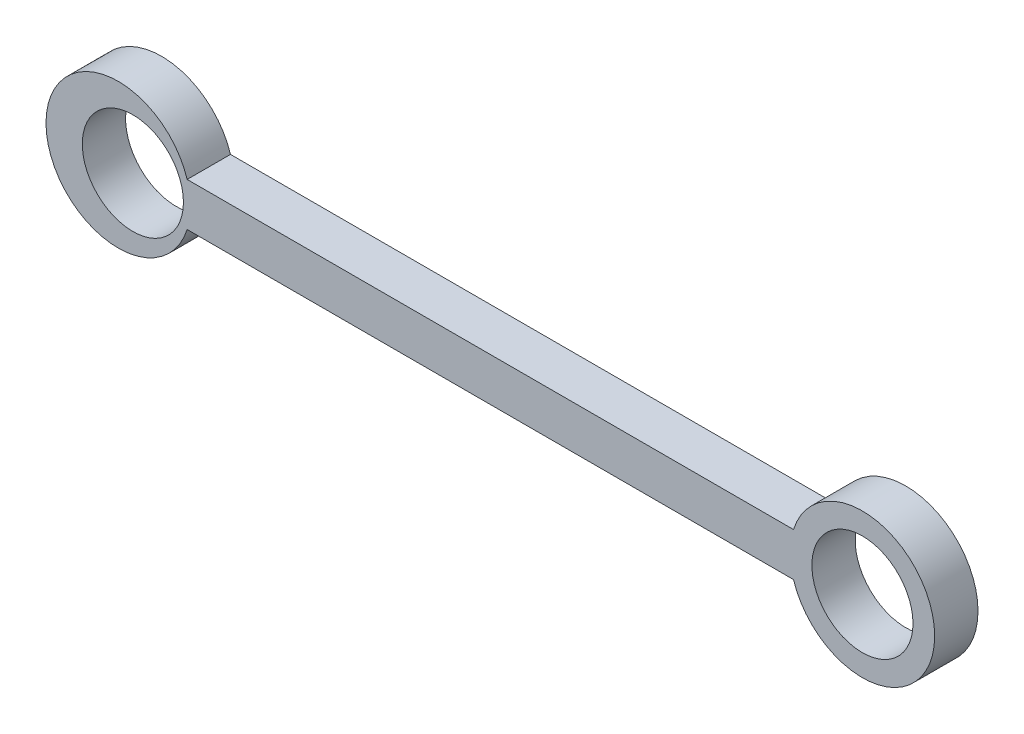
SolidWorks part; units mm, degrees
ref_plane "Front Plane" through (0, 0, 0) normal (0, 0, 1) x (1, 0, 0)
ref_plane "Top Plane" through (0, 0, 0) normal (0, 1, 0) x (1, 0, 0)
ref_plane "Right Plane" through (0, 0, 0) normal (1, 0, 0) x (0, 0, -1)
sketch "Sketch1" plane through (0, 0, 0) normal (0, 0, 1) x (1, 0, 0)
  line L3 (10.2402, 1.5) -> (-10.746, 1.5)
  line L4 (10.125, 0.75) -> (-10.875, 0.75) construction
  line L6 (10.2402, 0) -> (-10.746, 0)
  arc A0 (10.2402, 0) -> (10.2402, 1.5) centre (12.625, 0.75) ccw
  circle A1 centre (-12.625, 0.75) radius 1.75
  circle A2 centre (12.625, 0.75) radius 1.75
  arc A3 (-10.746, 1.5) -> (-10.746, 0) centre (-13.1308, 0.75) ccw
  point P0 (12.625, 1.5)
  point P1 (-12.625, 0)
  point P2 (12.625, 0)
  point P4 (0, 0)
  point P6 (-12.625, 1.5)
extrude "Boss-Extrude1" add sketch "Sketch1" along normal blind 1.5
